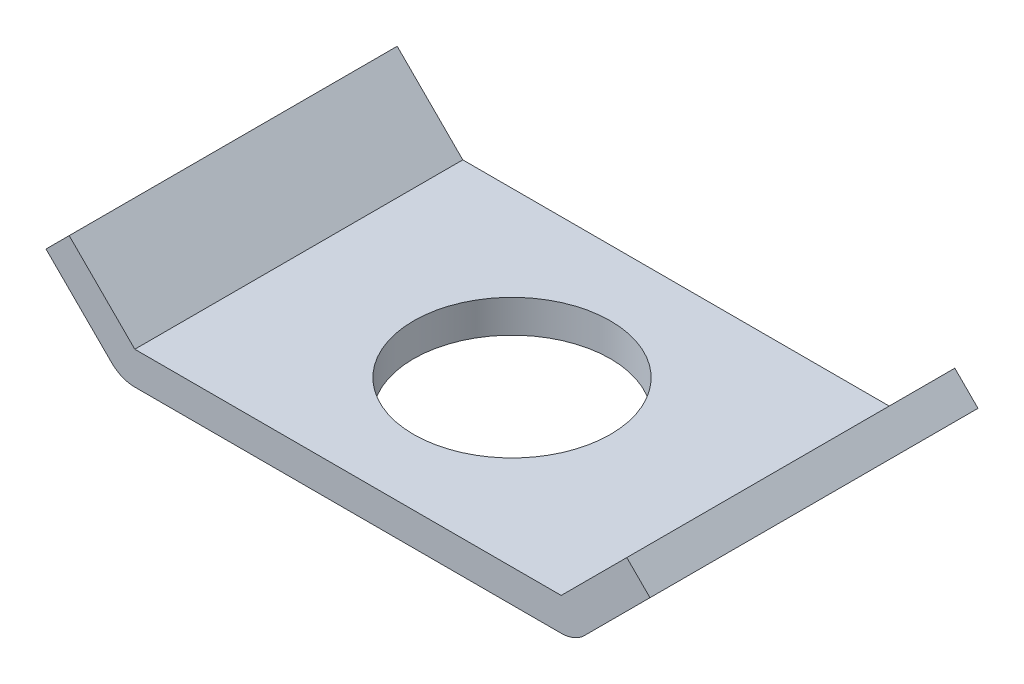
SolidWorks part; units mm, degrees
ref_plane "Front Plane" through (0, 0, 0) normal (0, 0, 1) x (1, 0, 0)
ref_plane "Top Plane" through (0, 0, 0) normal (0, 1, 0) x (1, 0, 0)
ref_plane "Right Plane" through (0, 0, 0) normal (1, 0, 0) x (0, 0, -1)
sketch "Sketch1" plane through (0, 0, 0) normal (0, 0, 1) x (1, 0, 0)
  line L0 (-3.25, 0) -> (3.25, 0)
  line L1 (3.25, 0) -> (4.25, 1)
  line L2 (-3.25, 0) -> (-4.25, 1)
  line L3 (0, 0) -> (0, 1.6785) construction
  line L4 (3.6036, -0.3536) -> (4.6036, 0.6464)
  line L5 (-3.25, -0.5) -> (3.25, -0.5)
  line L6 (-3.6036, -0.3536) -> (-4.6036, 0.6464)
  line L7 (-4.25, 1) -> (-4.6036, 0.6464)
  line L8 (4.25, 1) -> (4.6036, 0.6464)
  line L9 (-3.4571, -0.5) -> (3.4571, -0.5) construction
  line L10 (-3.4571, -0.5) -> (-4.6036, 0.6464) construction
  line L11 (3.4571, -0.5) -> (4.6036, 0.6464) construction
  arc A0 (-3.25, -0.5) -> (-3.6036, -0.3536) centre (-3.25, 0) cw
  arc A1 (3.6036, -0.3536) -> (3.25, -0.5) centre (3.25, 0) cw
  dimension "D5" = 0.5
  dimension "D1" = 135
  dimension "D2" = 1
  dimension "D3" = 6.5
  dimension "D4" = 0.5
extrude "Boss-Extrude1" add sketch "Sketch1" along normal mid plane 5
sketch "Sketch2" plane through (0, -0.5, 0) normal (0, -1, 0) x (1, 0, 0)
  circle A0 centre (0, 0) radius 1.5
  dimension "D1" = 3
extrude "Cut-Extrude1" cut sketch "Sketch2" against normal blind 5
